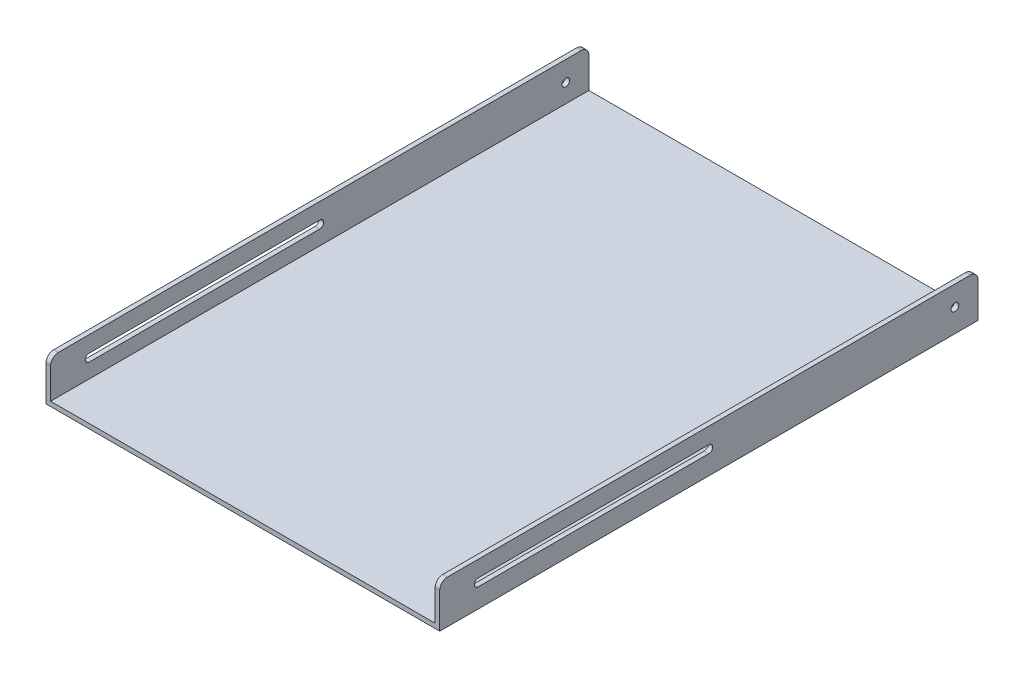
SolidWorks part; units mm, degrees
ref_plane "Front Plane" through (0, 0, 0) normal (0, 0, 1) x (1, 0, 0)
ref_plane "Top Plane" through (0, 0, 0) normal (0, 1, 0) x (1, 0, 0)
ref_plane "Right Plane" through (0, 0, 0) normal (1, 0, 0) x (0, 0, -1)
sketch "Sketch1" plane through (0, 0, 0) normal (0, 0, 1) x (1, 0, 0)
  line L0 (-250, 0) -> (-250, 50)
  line L1 (-250, 0) -> (250, 0)
  line L2 (250, 0) -> (250, 50)
  dimension "D1" = 500
  dimension "D2" = 50
extrude "Extrude-Thin1" add sketch "Sketch1" along normal mid plane 700 thin thin type one direction wall 6
sketch "Sketch2" plane through (256, 0, 0) normal (1, 0, 0) x (0, 0, -1)
  line L0 (0, 24) -> (-300, 24) construction
  line L1 (0, 19) -> (-300, 19)
  line L2 (0, 29) -> (-300, 29)
  line L3 (-350, -6) -> (350, -6) construction
  line L4 (350, -6) -> (350, 50) construction
  circle A0 centre (320, 24) radius 5
  arc A1 (0, 19) -> (0, 29) centre (0, 24) ccw
  arc A2 (-300, 29) -> (-300, 19) centre (-300, 24) ccw
  point P4 (-150, 24)
  dimension "D1" = 10
  dimension "D2" = 30
  dimension "D3" = 30
  dimension "D4" = 150
  dimension "D5" = 300
  dimension "D6" = 10
extrude "Cut-Extrude1" cut sketch "Sketch2" against normal through all
fillet "Fillet1" radius 10 4 edges at (-253, 50, -350) (253, 50, -350) (253, 50, 350) (-253, 50, 350)
